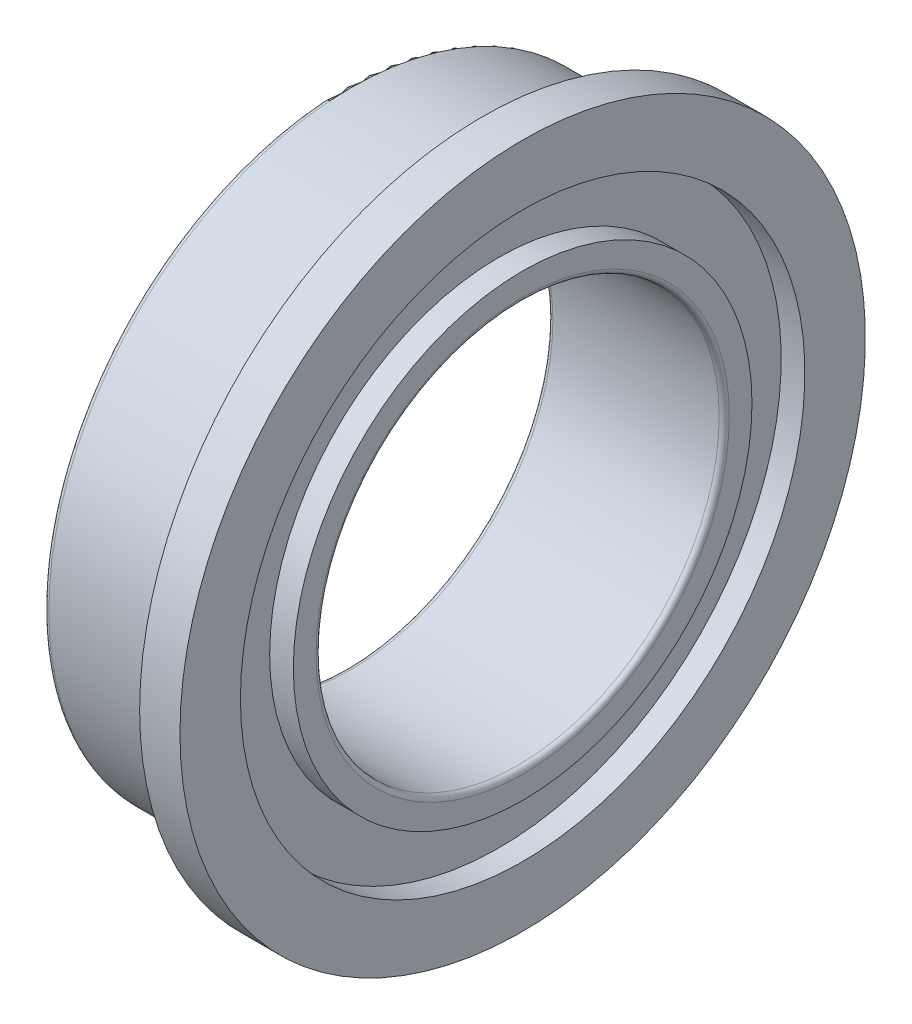
SolidWorks part; units mm, degrees
material "SUJ2"
ref_plane "Front Plane" through (0, 0, 0) normal (0, 0, 1) x (1, 0, 0)
ref_plane "Top Plane" through (0, 0, 0) normal (0, 1, 0) x (1, 0, 0)
ref_plane "Right Plane" through (0, 0, 0) normal (1, 0, 0) x (0, 0, -1)
sketch "Sketch1" plane through (0, 0, 0) normal (0, 0, 1) x (1, 0, 0)
  line L0 (-2.7, 0) -> (0.8, 0) construction
  line L1 (0, 6.2) -> (0, 6.8)
  line L2 (0, 6.8) -> (0.8, 6.8)
  line L3 (0.8, 6.8) -> (0.8, 5.6)
  line L4 (0.8, 4) -> (-2.7, 4)
  line L5 (-2.7, 4) -> (-2.7, 4.55)
  line L6 (-2.7, 6) -> (-0.2, 6)
  line L7 (-2.7, 5.6) -> (-2.23, 5.6)
  line L8 (-2.23, 5.6) -> (-2.23, 4.55)
  line L9 (-2.23, 4.55) -> (-2.7, 4.55)
  line L10 (0.8, 5.6) -> (0.33, 5.6)
  line L11 (0.33, 5.6) -> (0.33, 4.55)
  line L12 (0.33, 4.55) -> (0.8, 4.55)
  line L13 (-2.7, 5.6) -> (-2.7, 6)
  line L14 (0.8, 4.55) -> (0.8, 4)
  arc A0 (-0.2, 6) -> (0, 6.2) centre (0, 6) ccw
  dimension "FIX_1" = 0.2
  dimension "D_s" = 8
  dimension "C" = 0.8
  dimension "MSM_2" = 9.1
  dimension "MSM_1" = 11.2
  dimension "D" = 12
  dimension "D1." = 13.6
  dimension "B" = 3.5
  dimension "MSM_3" = 0.47
revolve "Revolve1" add sketch "Sketch1" angle 360 about L0
fillet "Fillet1" radius 0.1 3 edges at (0.8, 0, 4) (-2.7, 0, 4) (-2.7, 0, 6)
